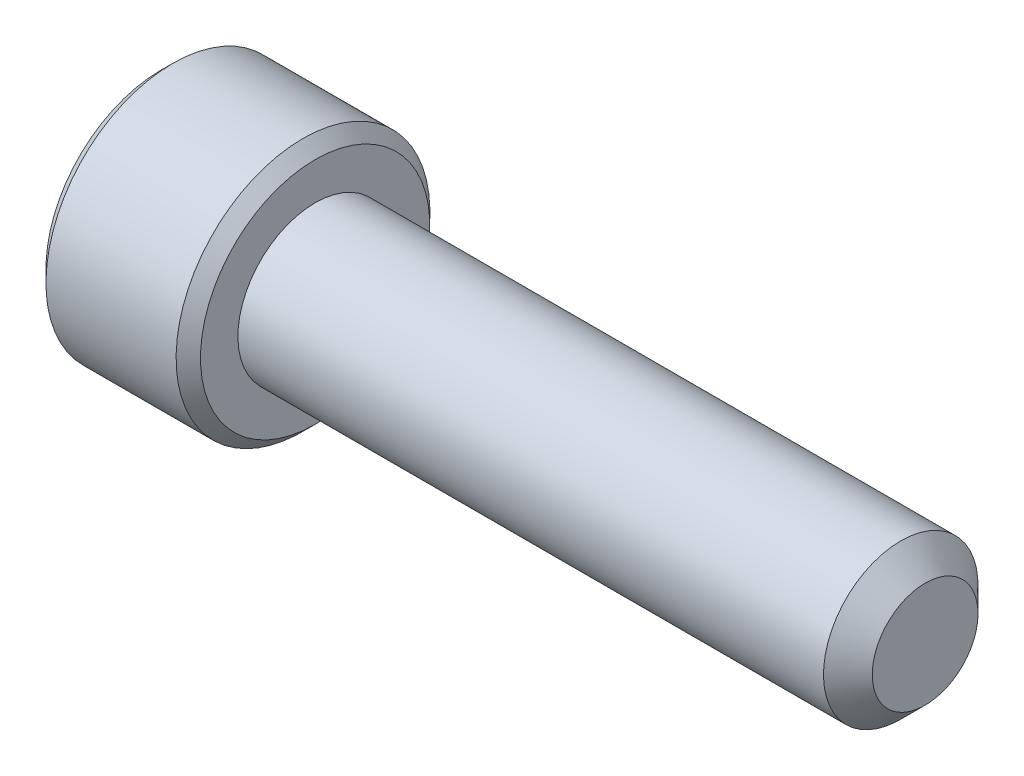
SolidWorks part; units mm, degrees
material "Plain Carbon Steel"
ref_plane "Front" through (0, 0, 0) normal (0, 0, 1) x (1, 0, 0)
ref_plane "Top" through (0, 0, 0) normal (0, 1, 0) x (1, 0, 0)
ref_plane "Right" through (0, 0, 0) normal (1, 0, 0) x (0, 0, -1)
sketch "Sketch1" plane through (0, 0, 0) normal (0, 0, 1) x (1, 0, 0)
  line L0 (0, 2.413) -> (0, 3.5814)
  line L1 (-0.381, 3.9624) -> (-4.445, 3.9624)
  line L2 (-4.826, 3.5814) -> (-4.826, 2.2914)
  line L3 (-2.5346, 0) -> (19.05, 0)
  line L4 (19.05, 0) -> (19.05, 1.651)
  line L5 (19.05, 1.651) -> (18.288, 2.413)
  line L6 (18.288, 2.413) -> (0, 2.413)
  line L7 (-2.5346, 0) -> (-4.826, 0) construction
  line L8 (0, 3.5814) -> (-0.381, 3.9624)
  line L9 (-4.826, 3.5814) -> (-4.445, 3.9624)
  line L10 (-4.826, 2.2914) -> (-2.5346, 0)
  line L11 (-5.8182, 1.7185) -> (-4.826, 2.2914) construction
  line L12 (-4.826, 2.2914) -> (-3.8338, 1.7185) construction
  circle A0 centre (-4.826, 0) radius 1.9844 construction
  dimension "D9" = 3.9688
  dimension "D1" = 4.826
  dimension "D2" = 4.826
  dimension "D3" = 7.9248
  dimension "D4" = 19.05
  dimension "D5" = 45
  dimension "D6" = 0.762
  dimension "D7" = 0.381
  dimension "D8" = 45
  dimension "D10" = 120
revolve "Revolve1" add sketch "Sketch1" angle 360 about L7
sketch "Sketch2" plane through (-4.826, 0, 0) normal (-1, 0, 0) x (0, 0, 1)
  line L1 (0, 2.2914) -> (-1.9844, 1.1457)
  line L2 (-1.9844, 1.1457) -> (-1.9844, -1.1457)
  line L3 (-1.9844, -1.1457) -> (0, -2.2914)
  line L4 (0, -2.2914) -> (1.9844, -1.1457)
  line L5 (1.9844, -1.1457) -> (1.9844, 1.1457)
  line L6 (1.9844, 1.1457) -> (0, 2.2914)
  circle A0 centre (0, 0) radius 1.9844 construction
  circle A1 centre (0, 0) radius 2.2914 construction
extrude "Cut-Extrude1" cut sketch "Sketch2" against normal blind 2.286
